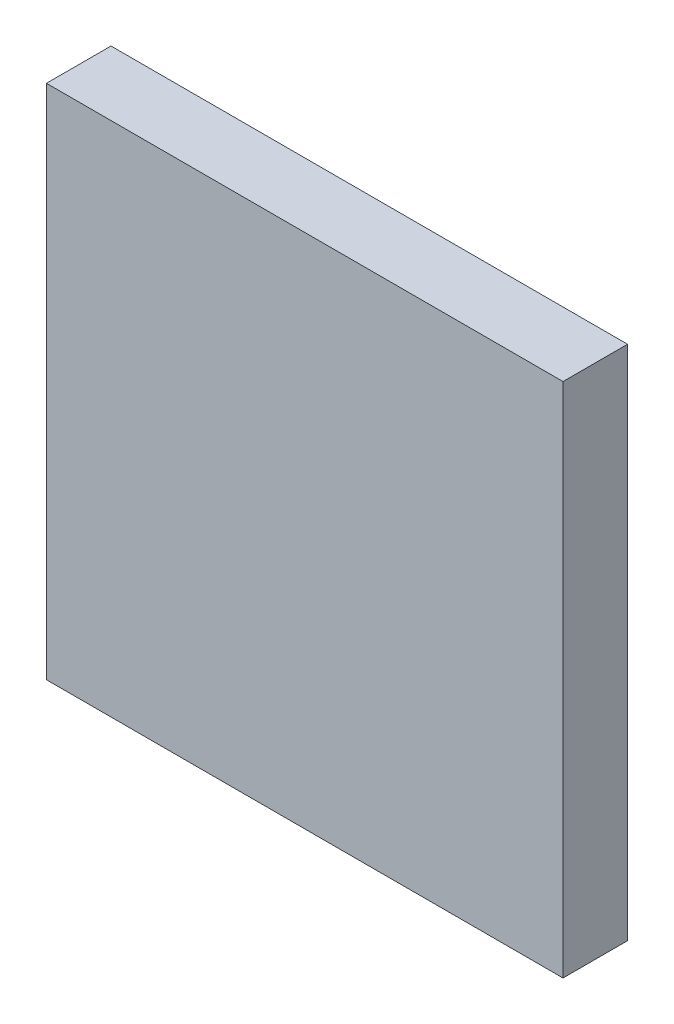
SolidWorks part; units mm, degrees
ref_plane "Front Plane" through (0, 0, 0) normal (0, 0, 1) x (1, 0, 0)
ref_plane "Top Plane" through (0, 0, 0) normal (0, 1, 0) x (1, 0, 0)
ref_plane "Right Plane" through (0, 0, 0) normal (1, 0, 0) x (0, 0, -1)
sketch "Sketch1" plane through (0, 0, 0) normal (0, 0, 1) x (1, 0, 0)
  line L1 (0, 0) -> (-25.4, 0)
  line L2 (0, 0) -> (0, 25.4)
  line L3 (0, 25.4) -> (-25.4, 25.4)
  line L4 (-25.4, 0) -> (-25.4, 25.4)
  dimension "D1" = 25.4
  dimension "D2" = 25.4
extrude "Boss-Extrude1" add sketch "Sketch1" along normal blind 3.175
